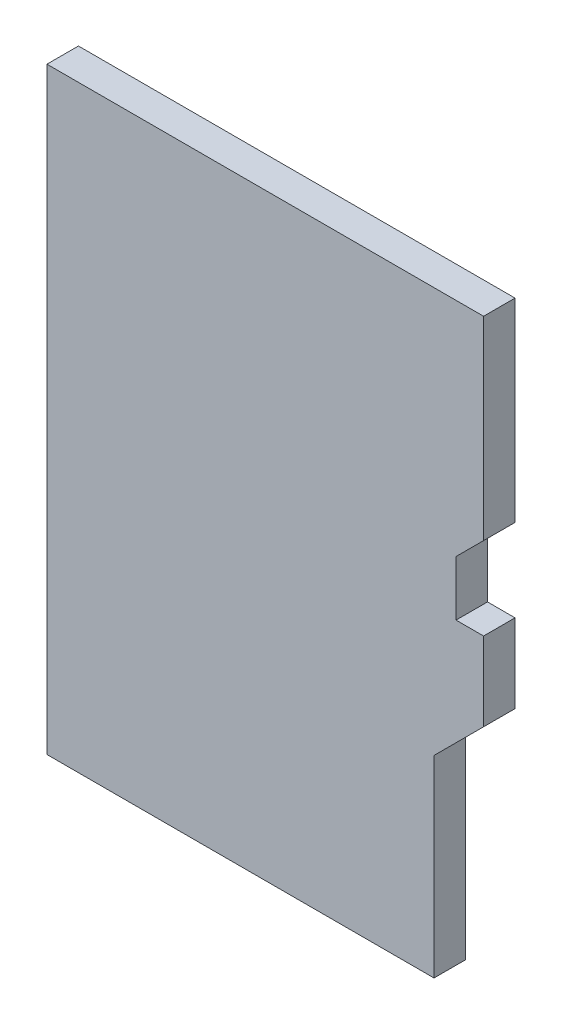
SolidWorks part; units mm, degrees
ref_plane "Alzado" through (0, 0, 0) normal (0, 0, 1) x (1, 0, 0)
ref_plane "Planta" through (0, 0, 0) normal (0, 1, 0) x (1, 0, 0)
ref_plane "Vista lateral" through (0, 0, 0) normal (1, 0, 0) x (0, 0, -1)
sketch "Croquis1" plane through (0, 0, 0) normal (0, 0, 1) x (1, 0, 0)
  line L0 (4.29, -2.7) -> (5.55, -1.44)
  line L1 (5.55, -7.6) -> (-5.55, -7.6)
  line L2 (5.55, -7.6) -> (5.55, 7.6)
  line L3 (5.55, 7.6) -> (-5.55, 7.6)
  line L4 (-5.55, -7.6) -> (-5.55, 7.6)
  line L5 (5.55, -7.6) -> (-5.55, 7.6) construction
  line L6 (5.55, 7.6) -> (-5.55, -7.6) construction
  line L7 (-5.55, -7.6) -> (4.29, -7.6)
  line L8 (-5.55, -7.6) -> (-5.55, -2.7)
  line L9 (-5.55, -2.7) -> (4.29, -2.7)
  line L10 (4.29, -7.6) -> (4.29, -2.7)
  line L11 (5.55, 0.56) -> (4.85, 0.56)
  line L12 (4.85, 0.56) -> (4.85, 1.96)
  line L13 (4.85, 1.96) -> (5.55, 2.66)
  point P0 (0, 0)
  dimension "D1" = 15.2
  dimension "D2" = 11.1
  dimension "D3" = 9.84
  dimension "D4" = 10.3
  dimension "D5" = 135
  dimension "D6" = 0.7
  dimension "D7" = 2
  dimension "D8" = 1.4
  dimension "D9" = 45
extrude "Saliente-Extruir1" add sketch "Croquis1" along normal blind 0.8 contours L12 L13 L2 L3 L4 L9 L0 L11 | L1 L10 L9 L4
